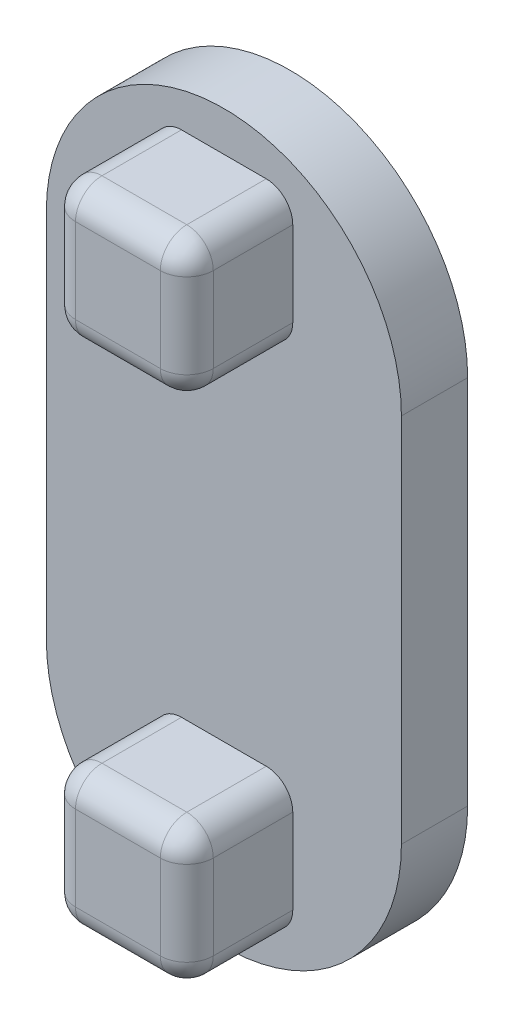
SolidWorks part; units mm, degrees
ref_plane "Front Plane" through (0, 0, 0) normal (1, 0, 0) x (0, 1, 0)
ref_plane "Top Plane" through (0, 0, 0) normal (0, 0, 1) x (0, 1, 0)
ref_plane "Right Plane" through (0, 0, 0) normal (0, 1, 0) x (-1, 0, 0)
sketch "Sketch1" plane through (0, 0, 0) normal (0, 0, 1) x (0, 1, 0)
  line L0 (0, 0) -> (14, 0) construction
  line L5 (0, 6.7) -> (14, 6.7)
  line L6 (0, -6.7) -> (14, -6.7)
  arc A0 (0, 6.7) -> (0, -6.7) centre (0, 0) ccw
  arc A1 (14, -6.7) -> (14, 6.7) centre (14, 0) ccw
  point P2 (7, 0)
  dimension "D1" = 14
  dimension "D2" = 13.4
extrude "Boss-Extrude1" add sketch "Sketch1" along normal blind 2.5
sketch "Sketch2" plane through (0, 0, 2.5) normal (0, 0, 1) x (1, 0, 0)
  line L0 (0, 0) -> (0, 14) construction
  line L1 (-2.6, 0) -> (2.6, 0)
  line L2 (-2.6, 0) -> (-2.6, -5.2)
  line L3 (-2.6, -5.2) -> (2.6, -5.2)
  line L4 (2.6, 0) -> (2.6, -5.2)
  line L5 (0, 7) -> (-6.7, 7) construction
  line L6 (-6.7, 0) -> (-6.7, 14) construction
  line L7 (2.6, 14) -> (2.6, 19.2)
  line L8 (-2.6, 19.2) -> (2.6, 19.2)
  line L9 (-2.6, 14) -> (-2.6, 19.2)
  line L10 (-2.6, 14) -> (2.6, 14)
  dimension "D1" = 5.2
  dimension "D2" = 5.2
  dimension "D3" = 2.6
  dimension "D4" = 0
extrude "Boss-Extrude2" add sketch "Sketch2" along normal blind 4
fillet "Fillet1" radius 1 16 edges at (0, 0, 6.5) (2.6, -2.6, 6.5) (-2.6, -2.6, 6.5) (0, -5.2, 6.5) (2.6, 0, 4.5) (-2.6, 0, 4.5) (-2.6, -5.2, 4.5) (2.6, -5.2, 4.5) (-2.6, 16.6, 6.5) (-2.6, 14, 4.5) (0, 14, 6.5) (0, 19.2, 6.5) (-2.6, 19.2, 4.5) (2.6, 14, 4.5) (2.6, 16.6, 6.5) (2.6, 19.2, 4.5)
